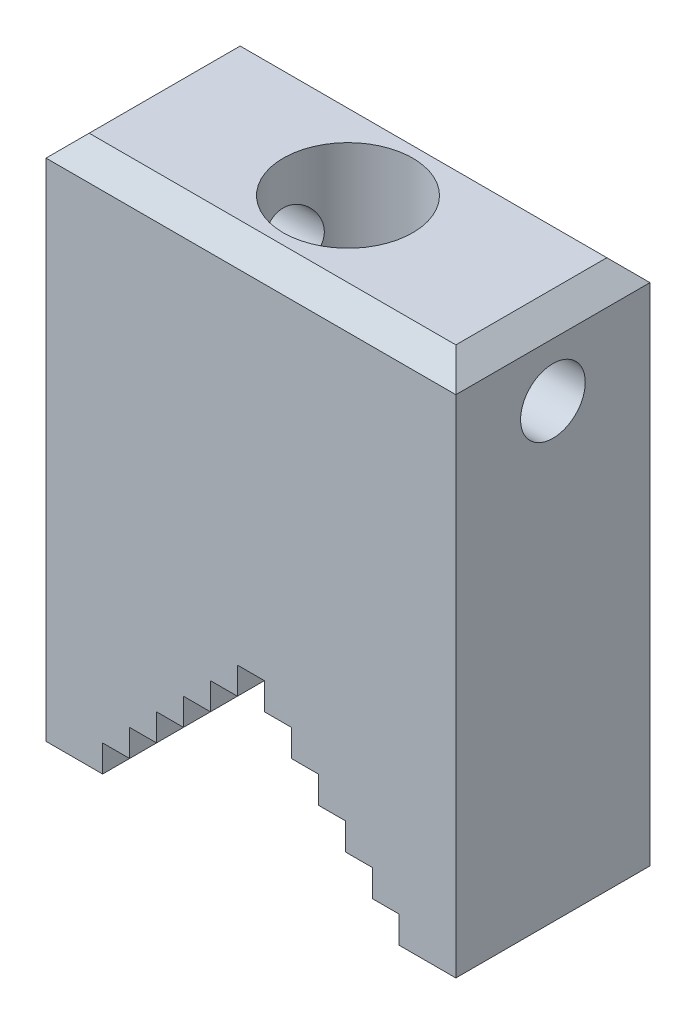
SolidWorks part; units mm, degrees
ref_plane "Front Plane" through (0, 0, 0) normal (0, 0, 1) x (1, 0, 0)
ref_plane "Top Plane" through (0, 0, 0) normal (0, 1, 0) x (1, 0, 0)
ref_plane "Right Plane" through (0, 0, 0) normal (1, 0, 0) x (0, 0, -1)
sketch "Sketch1" plane through (0, 0, 0) normal (0, 0, 1) x (1, 0, 0)
  line L0 (-13.75, -24.4196) -> (-13.75, -21.9196)
  line L1 (-19, -24.4196) -> (-13.75, -24.4196)
  line L2 (-19, -24.4196) -> (-19, 24.4196)
  line L3 (-19, 24.4196) -> (19, 24.4196)
  line L4 (19, -24.4196) -> (19, 24.4196)
  line L5 (-19, -24.4196) -> (19, 24.4196) construction
  line L6 (-19, 24.4196) -> (19, -24.4196) construction
  line L7 (-13.75, -21.9196) -> (-11.25, -21.9196)
  line L8 (-11.25, -21.9196) -> (-11.25, -19.4196)
  line L9 (-11.25, -19.4196) -> (-8.75, -19.4196)
  line L10 (-8.75, -19.4196) -> (-8.75, -16.9196)
  line L11 (-8.75, -16.9196) -> (-6.25, -16.9196)
  line L12 (-6.25, -16.9196) -> (-6.25, -14.4196)
  line L13 (-6.25, -14.4196) -> (-3.75, -14.4196)
  line L14 (-3.75, -14.4196) -> (-3.75, -11.9196)
  line L15 (-3.75, -11.9196) -> (-1.25, -11.9196)
  line L16 (-1.25, -11.9196) -> (-1.25, -9.4196)
  line L17 (-1.25, -9.4196) -> (1.25, -9.4196)
  line L18 (0, 0) -> (0, 50000) construction
  line L19 (1.25, -9.4196) -> (1.25, -11.9196)
  line L20 (1.25, -11.9196) -> (3.75, -11.9196)
  line L21 (3.75, -11.9196) -> (3.75, -14.4196)
  line L22 (3.75, -14.4196) -> (6.25, -14.4196)
  line L23 (6.25, -14.4196) -> (6.25, -16.9196)
  line L24 (6.25, -16.9196) -> (8.75, -16.9196)
  line L25 (8.75, -16.9196) -> (8.75, -19.4196)
  line L26 (8.75, -19.4196) -> (11.25, -19.4196)
  line L27 (11.25, -19.4196) -> (11.25, -21.9196)
  line L28 (11.25, -21.9196) -> (13.75, -21.9196)
  line L29 (13.75, -21.9196) -> (13.75, -24.4196)
  line L30 (13.75, -24.4196) -> (19, -24.4196)
  point P0 (0, 0)
  dimension "D1" = 2.5
  dimension "D2" = 2.5
  dimension "D3" = 5.25
  dimension "D4" = 38
  dimension "D5" = 2.5
  dimension "D6" = 2.5
  dimension "D7" = 5.25
  dimension "D8" = 2.5
  dimension "D9" = 2.5
  dimension "D10" = 2.5
  dimension "D11" = 2.5
  dimension "D12" = 2.5
  dimension "D13" = 2.5
extrude "Boss-Extrude1" add sketch "Sketch1" along normal blind 18
chamfer "Chamfer1" distance 2 angle 45 4 edges at (19, 24.4196, 9) (0, 24.4196, 18) (-19, 24.4196, 9) (0, 24.4196, 0)
sketch "Sketch3" plane through (19, 0, 0) normal (1, 0, 0) x (0, 0, -1)
  line L0 (-16, 24.4196) -> (-2, 24.4196) construction
  line L1 (-18, -24.4196) -> (-18, 22.4196) construction
  circle A0 centre (-9, 17.4196) radius 3
  point P6 (0, 0)
  dimension "D1" = 6
  dimension "D2" = 7
  dimension "D3" = 9
extrude "Cut-Extrude1" cut sketch "Sketch3" against normal through all both and the other way through all
hole_wizard "Ø1.0mm Dowel Hole1" positions "Sketch6" profile "Sketch5" hole size "Ø1.0" standard "ISO"
sketch "Sketch6" plane through (0, 24.4196, 0) normal (0, 1, 0) x (1, 0, 0)
  line L1 (-19, 0) -> (19, 0) construction
  point P0 (0, -9)
  point P7 (0, 0)
  dimension "D1" = 9
sketch "Sketch5" plane through (0, 24.4196, 9) normal (1, 0, 0) x (0, 0, 1)
  line L0 (0, 0) -> (0, 23.4641)
  line L1 (0, 23.4641) -> (6, 20)
  line L2 (6, 20) -> (6, 0)
  line L5 (6, 0) -> (0, 0)
  line L10 (0, 23.4641) -> (-6, 20) construction
  line L11 (0, -6.35) -> (0, 107.95) construction
  dimension "Hole Dia." = 12
  dimension "Hole Depth" = 20
  dimension "Drill Angle" = 120
